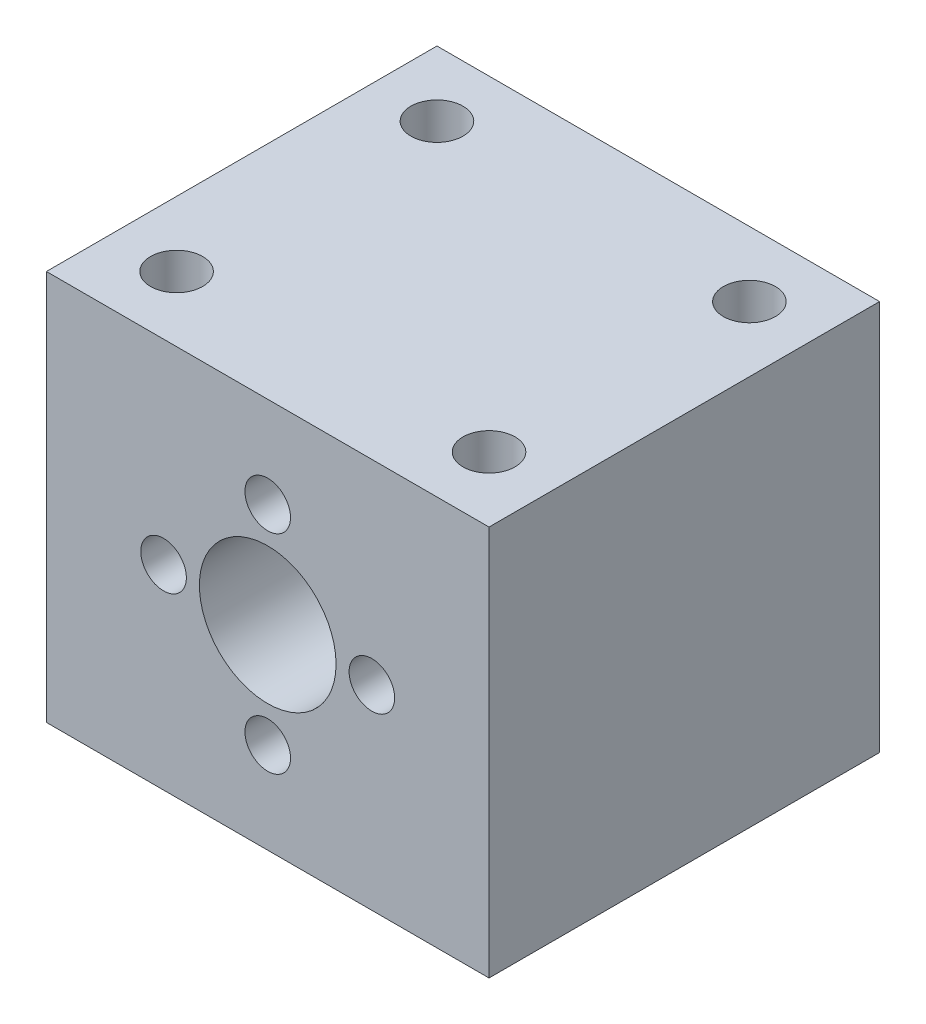
SolidWorks part; units mm, degrees
ref_plane "前视基准面" through (0, 0, 0) normal (0, 0, 1) x (1, 0, 0)
ref_plane "上视基准面" through (0, 0, 0) normal (0, 1, 0) x (1, 0, 0)
ref_plane "右视基准面" through (0, 0, 0) normal (1, 0, 0) x (0, 0, -1)
sketch "草图1" plane through (0, 0, 0) normal (0, 0, 1) x (1, 0, 0)
  line L1 (17, 15) -> (-17, 15)
  line L2 (17, 15) -> (17, -15)
  line L3 (17, -15) -> (-17, -15)
  line L4 (-17, 15) -> (-17, -15)
  circle A0 centre (0, 0) radius 5.25
  point P0 (0, 0)
  point P19 (0, 0)
  dimension "D1" = 34
  dimension "D2" = 30
extrude "凸台-拉伸1" add sketch "草图1" along normal blind 30
sketch "草图2" plane through (0, 0, 30) normal (0, 0, 1) x (1, 0, 0)
  circle A0 centre (-8, 0) radius 1.75
  circle A1 centre (0, 8) radius 1.75
  circle A2 centre (8, 0) radius 1.75
  circle A3 centre (0, -8) radius 1.75
  point P12 (0, 0)
  dimension "D1" = 8
  dimension "D2" = 4
extrude "切除-拉伸1" cut sketch "草图2" against normal blind 10
sketch "草图4" plane through (0, 15, 0) normal (0, 1, 0) x (1, 0, 0)
  line L0 (17, -30) -> (-17, -30) construction
  line L1 (17, -30) -> (17, 0) construction
  circle A0 centre (12, -25) radius 2
  circle A1 centre (-12, -25) radius 2
  circle A2 centre (-12, -5) radius 2
  circle A3 centre (12, -5) radius 2
  dimension "D1" = 24
  dimension "D2" = 24
  dimension "D3" = 20
  dimension "D4" = 5
  dimension "D5" = 5
  dimension "D6" = 5
extrude "切除-拉伸3" cut sketch "草图4" against normal blind 10
